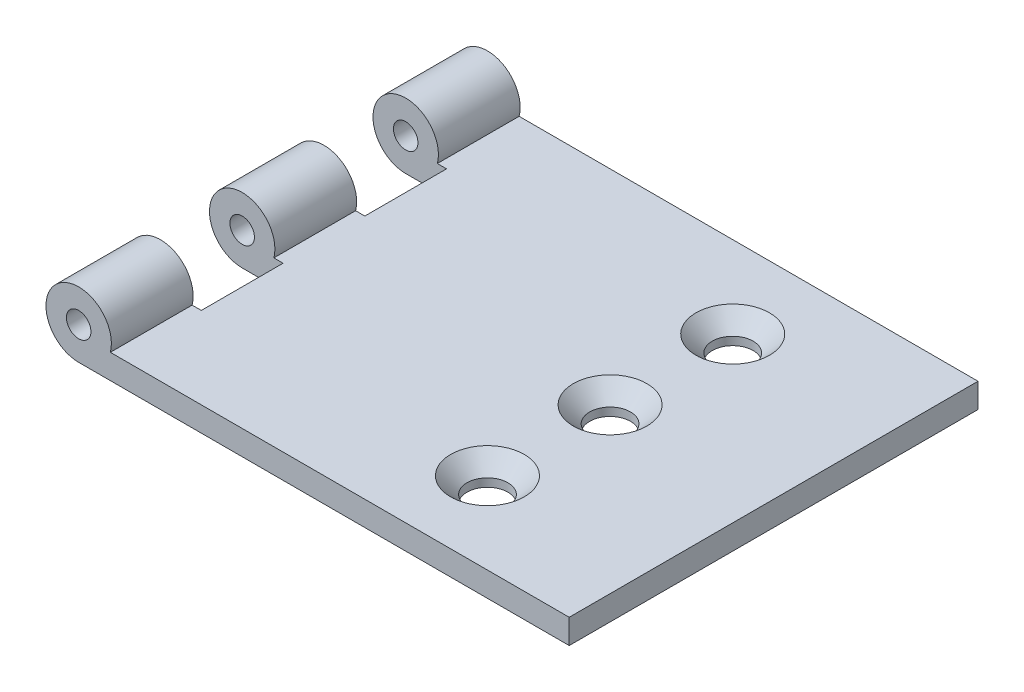
SolidWorks part; units mm, degrees
ref_plane "前视基准面" through (0, 0, 0) normal (0, 0, 1) x (1, 0, 0)
ref_plane "上视基准面" through (0, 0, 0) normal (0, 1, 0) x (1, 0, 0)
ref_plane "右视基准面" through (0, 0, 0) normal (1, 0, 0) x (0, 0, -1)
sketch "草图1" plane through (0, 0, 0) normal (0, 1, 0) x (1, 0, 0)
  line L0 (0, 25) -> (60, 25)
  line L1 (60, 25) -> (60, -25)
  line L2 (60, -25) -> (0, -25)
  line L3 (0, -25) -> (0, -15)
  line L4 (0, -15) -> (5, -15)
  line L5 (5, -15) -> (5, -5)
  line L6 (5, -5) -> (0, -5)
  line L7 (0, -5) -> (0, 5)
  line L8 (0, 5) -> (5, 5)
  line L9 (5, 5) -> (5, 15)
  line L10 (5, 15) -> (0, 15)
  line L11 (0, 15) -> (0, 25)
extrude "凸台-拉伸1" add sketch "草图1" along normal blind 3
ref_plane "基准面1" through (0, 0, -25) normal (0, 0, 1) x (1, 0, 0)
sketch "草图2" plane through (0, 0, -25) normal (0, 0, 1) x (1, 0, 0)
  circle A0 centre (0, 4) radius 4
extrude "凸台-拉伸2" add sketch "草图2" along normal blind 10
pattern_linear "阵列(线性)1" count 3 spacing 20 along (0, 0, 1) of "凸台-拉伸2"
sketch "草图3" plane through (0, 0, -25) normal (0, 0, 1) x (1, 0, 0)
  circle A0 centre (0, 4) radius 1.5
extrude "切除-拉伸1" cut sketch "草图3" against normal mid plane 130
ref_plane "基准面2" through (0, 3, 0) normal (0, 1, 0) x (1, 0, 0)
sketch "草图4" plane through (0, 3, 0) normal (0, 1, 0) x (1, 0, 0)
  circle A0 centre (40, 15) radius 2.5
  circle A1 centre (40, 0) radius 2.5
  circle A2 centre (40, -15) radius 2.5
extrude "切除-拉伸2" cut sketch "草图4" against normal through all
ref_plane "基准面3" through (0, 0.5, 0) normal (0, 1, 0) x (1, 0, 0)
ref_plane "基准面4" through (40, 0, 0) normal (1, 0, 0) x (0, 0, -1)
sketch "草图10" plane through (40, 0, 0) normal (1, 0, 0) x (0, 0, -1)
  line L0 (15, 0) -> (15, 8) construction
  line L1 (12.5, 3) -> (10.5, 3)
  line L2 (10.5, 3) -> (12.5, 1)
  line L3 (12.5, 1) -> (12.5, 3)
revolve "切除-旋转1" cut sketch "草图10" angle 360 about L0
sketch "草图11" plane through (40, 0, 0) normal (1, 0, 0) x (0, 0, -1)
  line L0 (0, 0) -> (0, 8) construction
  line L1 (-2.5, 3) -> (-4.5, 3)
  line L2 (-4.5, 3) -> (-2.5, 1)
  line L3 (-2.5, 1) -> (-2.5, 3)
revolve "切除-旋转2" cut sketch "草图11" angle 360 about L0
sketch "草图12" plane through (40, 0, 0) normal (1, 0, 0) x (0, 0, -1)
  line L0 (-15, 0) -> (-15, 8) construction
  line L1 (-17.5, 3) -> (-19.5, 3)
  line L2 (-19.5, 3) -> (-17.5, 1)
  line L3 (-17.5, 1) -> (-17.5, 3)
revolve "切除-旋转3" cut sketch "草图12" angle 360 about L0
